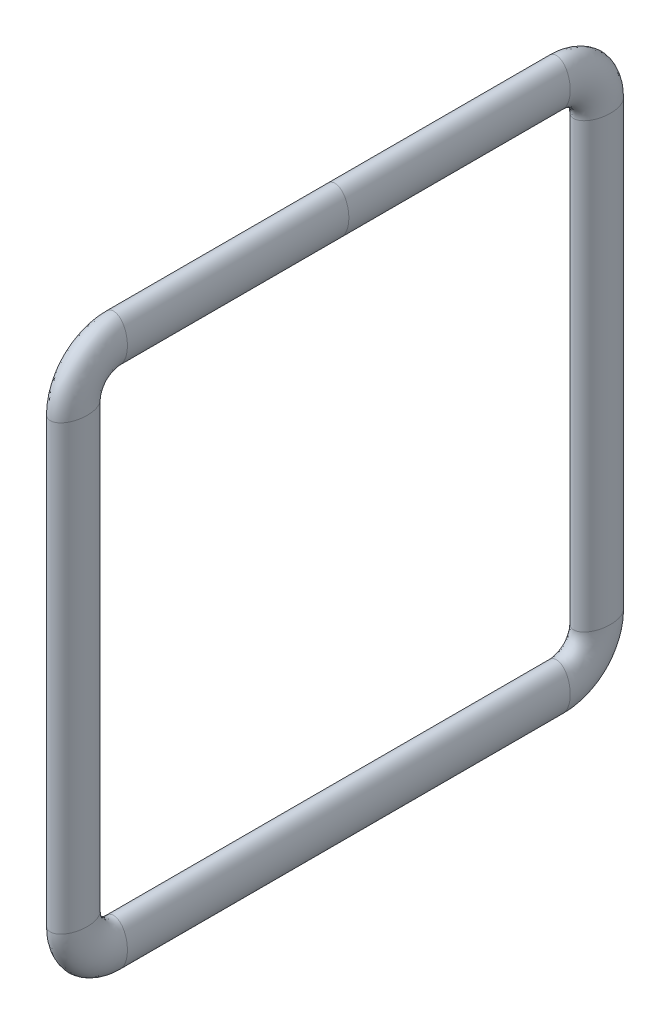
SolidWorks part; units mm, degrees
material "ｺﾞﾑ"
ref_plane "Front Plane" through (0, 0, 0) normal (0, 0, 1) x (1, 0, 0)
ref_plane "Top Plane" through (0, 0, 0) normal (0, 1, 0) x (1, 0, 0)
ref_plane "Right Plane" through (0, 0, 0) normal (1, 0, 0) x (0, 0, -1)
sketch "ｽｹｯﾁ1" plane through (0, 0, 0) normal (0, 0, 1) x (1, 0, 0)
  line L0 (0, 23.3) -> (0, 0) construction
  line L1 (0, 0) -> (18.7324, 0) construction
  circle A0 centre (0, 23.3) radius 1.55
  ellipse E0 centre (0, 23.3) end of major axis (0, 25.3) minor radius 1.2
  point P7 (0, 21.75)
  dimension "D1" = 3.1
  dimension "D2" = 2.4
  dimension "D3" = 2
  dimension "D4" = 21.75
revolve "回転2" [suppressed] add sketch "ｽｹｯﾁ1" angle 360 about L1
sketch "ｽｹｯﾁ3" plane through (0, 0, 0) normal (1, 0, 0) x (0, 0, -1)
  line L0 (0, 0) -> (18.2582, 0) construction
  line L1 (-19.25, 22.75) -> (19.25, 22.75)
  line L2 (-19.25, -22.75) -> (19.25, -22.75)
  line L3 (22.75, 19.25) -> (22.75, -19.25)
  line L4 (0, 23.3) -> (0, 0) construction
  line L5 (0, 0) -> (0, 16.3049) construction
  line L6 (-22.75, 19.25) -> (-22.75, -19.25)
  arc A0 (19.25, 22.75) -> (22.75, 19.25) centre (19.25, 19.25) cw
  arc A1 (19.25, -22.75) -> (22.75, -19.25) centre (19.25, -19.25) ccw
  arc A2 (-19.25, -22.75) -> (-22.75, -19.25) centre (-19.25, -19.25) cw
  arc A3 (-19.25, 22.75) -> (-22.75, 19.25) centre (-19.25, 19.25) ccw
  point P7 (0, 0)
  point P9 (13.0238, 21.25)
  point P12 (18.4176, 21.25)
  point P13 (19.3082, 21.25)
  point P22 (-21.25, 19.862)
  dimension "D2" = 3.5
  dimension "D1" = 45.5
sketch "ｽｹｯﾁ4" plane through (0, 0, 0) normal (0, 0, 1) x (1, 0, 0)
  line L0 (0, 24.75) -> (0, 20.75) construction
  ellipse E0 centre (0, 22.75) end of major axis (0, 24.75) minor radius 1.2
  point P8 (0, 0)
  dimension "D1" = 4
  dimension "D2" = 2.4
sweep "ｽｲｰﾌﾟ1" add profiles "ｽｹｯﾁ4" path "ｽｹｯﾁ3"
